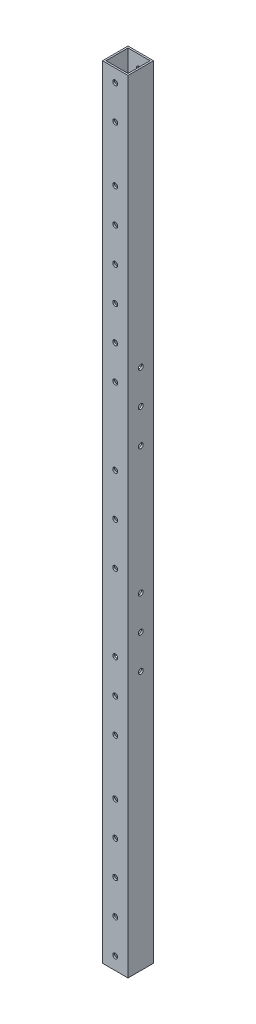
SolidWorks part; units mm, degrees
material "Thornel Mat VMA"
ref_plane "前视基准面" through (0, 0, 0) normal (0, 0, 1) x (1, 0, 0)
ref_plane "上视基准面" through (0, 0, 0) normal (0, 1, 0) x (1, 0, 0)
ref_plane "右视基准面" through (0, 0, 0) normal (1, 0, 0) x (0, 0, -1)
sketch "草图1" plane through (0, 0, 0) normal (0, 1, 0) x (1, 0, 0)
  line L1 (-7.5, -7.5) -> (7.5, -7.5)
  line L2 (-7.5, -7.5) -> (-7.5, 7.5)
  line L3 (-7.5, 7.5) -> (7.5, 7.5)
  line L4 (7.5, -7.5) -> (7.5, 7.5)
  line L5 (-7.5, -7.5) -> (7.5, 7.5) construction
  line L6 (-7.5, 7.5) -> (7.5, -7.5) construction
  point P0 (0, 0)
  dimension "D1" = 15
  dimension "D2" = 15
extrude "拉伸-薄壁1" add sketch "草图1" along normal blind 460 thin thin type one direction reverse wall 1
sketch "草图2" plane through (0, 0, 7.5) normal (0, 0, 1) x (1, 0, 0)
  line L0 (0, 0) -> (0, 460) construction
  line L1 (-7.5, 460) -> (7.5, 460) construction
  line L2 (-1000, 230) -> (49000, 230) construction
  line L3 (-7.5, 0) -> (7.5, 0) construction
  circle A0 centre (0, 7.5) radius 1.45
  circle A1 centre (0, 27.5) radius 1.45
  circle A2 centre (0, 432.5) radius 1.45
  circle A3 centre (0, 452.5) radius 1.45
  circle A4 centre (0, 140) radius 1.45
  circle A5 centre (0, 160) radius 1.45
  circle A6 centre (0, 120) radius 1.45
  circle A7 centre (0, 340) radius 1.45
  circle A8 centre (0, 300) radius 1.45
  circle A9 centre (0, 320) radius 1.45
  circle A10 centre (0, 230) radius 1.45
  circle A11 centre (0, 255) radius 1.45
  circle A12 centre (0, 205) radius 1.45
  circle A13 centre (0, 47.5) radius 1.45
  circle A14 centre (0, 67.5) radius 1.45
  circle A15 centre (0, 87.5) radius 1.45
  circle A16 centre (0, 360) radius 1.45
  circle A17 centre (0, 380) radius 1.45
  circle A18 centre (0, 400) radius 1.45
  point P8 (0, 230)
  dimension "D1" = 2.9
  dimension "D4" = 2.9
  dimension "D6" = 20
  dimension "D7" = 90
  dimension "D8" = 25
  dimension "D9" = 25
  dimension "D10" = 20
  dimension "D11" = 20
  dimension "D12" = 20
  dimension "D13" = 20
  dimension "D14" = 20
  dimension "D15" = 130
  dimension "D2" = 7.5
  dimension "D3" = 20
  dimension "D5" = 20
extrude "切除-拉伸1" cut sketch "草图2" against normal through all
sketch "草图3" plane through (7.5, 0, 0) normal (1, 0, 0) x (0, 0, -1)
  line L0 (0, 0) -> (0, 460) construction
  line L1 (-7.5, 460) -> (7.5, 460) construction
  line L2 (-1000, 230) -> (49000, 230) construction
  circle A0 centre (0, 152.5) radius 1.45
  circle A1 centre (0, 172.5) radius 1.45
  circle A2 centre (0, 287.5) radius 1.45
  circle A3 centre (0, 307.5) radius 1.45
  circle A4 centre (0, 192.5) radius 1.45
  circle A5 centre (0, 267.5) radius 1.45
  point P12 (0, 230)
  dimension "D3" = 2.9
  dimension "D1" = 20
  dimension "D2" = 20
  dimension "D4" = 115
extrude "切除-拉伸2" cut sketch "草图3" against normal through all
